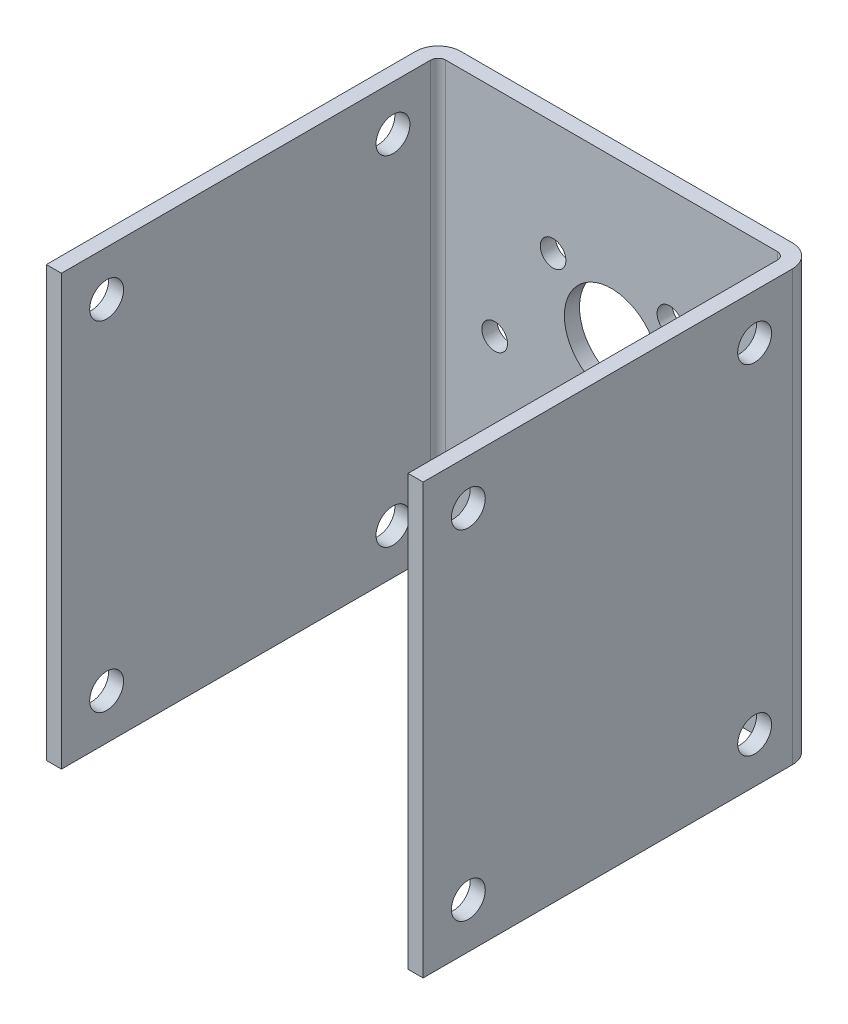
SolidWorks part; units mm, degrees
material "ABS"
ref_plane "Front Plane" through (0, 0, 0) normal (0, 0, 1) x (1, 0, 0)
ref_plane "Top Plane" through (0, 0, 0) normal (0, 1, 0) x (1, 0, 0)
ref_plane "Right Plane" through (0, 0, 0) normal (1, 0, 0) x (0, 0, -1)
sketch "Sketch1" plane through (0, 0, 0) normal (0, 1, 0) x (1, 0, 0)
  line L0 (-2, 0) -> (-2, 49)
  line L1 (1, 52) -> (45, 52)
  line L2 (48, 49) -> (48, 0)
  line L3 (48, 0) -> (46, 0)
  line L4 (46, 0) -> (46, 49)
  line L5 (45, 50) -> (1, 50)
  line L6 (0, 49) -> (0, 0)
  line L7 (0, 0) -> (-2, 0)
  arc A0 (45, 52) -> (48, 49) centre (45, 49) cw
  arc A1 (-2, 49) -> (1, 52) centre (1, 49) cw
  arc A2 (46, 49) -> (45, 50) centre (45, 49) ccw
  arc A3 (1, 50) -> (0, 49) centre (1, 49) ccw
  point P12 (48, 52)
  point P15 (-2, 52)
  dimension "D6" = 3
  dimension "D7" = 1
  dimension "D1" = 52
  dimension "D2" = 2
  dimension "D3" = 2
  dimension "D4" = 2
  dimension "D5" = 50
extrude "Boss-Extrude1" add sketch "Sketch1" along normal blind 57
sketch "Sketch2" plane through (48, 0, 0) normal (1, 0, 0) x (0, 0, -1)
  line L0 (0, 51) -> (52, 51) construction
  line L1 (0, 57) -> (0, 0) construction
  line L2 (52, 57) -> (52, 0) construction
  line L3 (0, 6) -> (52, 6) construction
  line L4 (0, 57) -> (49, 57) construction
  line L5 (0, 0) -> (49, 0) construction
  circle A0 centre (6, 51) radius 2.25
  circle A1 centre (44, 51) radius 2.25
  circle A2 centre (6, 6) radius 2.25
  circle A3 centre (44, 6) radius 2.25
  dimension "D3" = 4.5
  dimension "D4" = 4.5
  dimension "D5" = 4.5
  dimension "D6" = 4.5
  dimension "D1" = 6
  dimension "D2" = 6
  dimension "D7" = 6
  dimension "D8" = 8
extrude "Cut-Extrude1" cut sketch "Sketch2" against normal through all
sketch "Sketch3" plane through (0, 0, -52) normal (0, 0, -1) x (-1, 0, 0)
  line L0 (-23, 57) -> (-23, 0) construction
  line L1 (-45, 57) -> (-1, 57) construction
  line L2 (-45, 0) -> (-1, 0) construction
  line L3 (-23, 28.5) -> (-38.5, 28.5) construction
  circle A0 centre (-23, 28.5) radius 15.5 construction
  circle A1 centre (-38.5, 28.5) radius 1.7
  circle A2 centre (-30.75, 41.9234) radius 1.7
  circle A3 centre (-15.25, 41.9234) radius 1.7
  circle A4 centre (-7.5, 28.5) radius 1.7
  circle A5 centre (-15.25, 15.0766) radius 1.7
  circle A6 centre (-30.75, 15.0766) radius 1.7
  circle A7 centre (-23, 35.5) radius 6.25
  point P25 (-23, 28.5)
  dimension "D1" = 31
  dimension "D2" = 3.4
  dimension "D4" = 7
  dimension "D5" = 12.5
  dimension "D3" = 6
extrude "Cut-Extrude2" cut sketch "Sketch3" against normal blind 52
